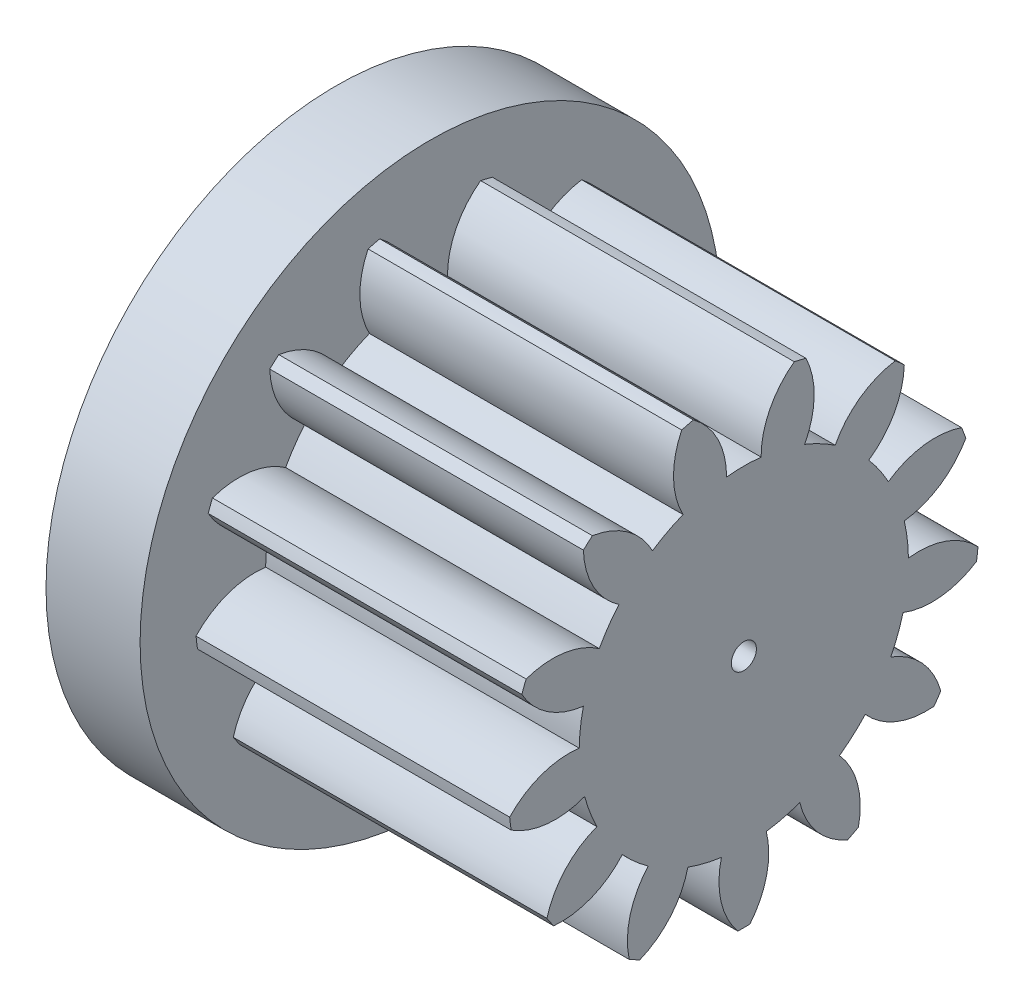
SolidWorks part; units mm, degrees
ref_plane "Plane1" through (0, 0, 0) normal (0, 0, 1) x (1, 0, 0)
ref_plane "Plane2" through (0, 0, 0) normal (0, 1, 0) x (1, 0, 0)
ref_plane "Plane3" through (0, 0, 0) normal (1, 0, 0) x (0, 0, -1)
sketch "HoldingSke" plane through (0, 0, 0) normal (0, 1, 0) x (1, 0, 0)
  line L0 (0, 0) -> (0.9744, -0.225)
  line L1 (-15, 0) -> (100, 0) construction
  line L2 (0, 0) -> (-2.1039, 2.3779)
  line L3 (0, 0) -> (-11.863, 4.5341)
  line L4 (0, 0) -> (8.4147, 1.9427)
  line L5 (0, 0) -> (-46.8476, -17.4728)
  line L6 (0, 0) -> (-8.2896, -5.593)
  line L7 (-2.1039, 2.3779) -> (8.6586, 51.2059)
  line L8 (-76.2, 54.61) -> (-76.1, 54.61)
  line L9 (-71.009, 38.7566) -> (-53.1078, 45.2721)
  line L10 (-76.2, 71.12) -> (104.1128, 71.12)
  line L11 (0, 0) -> (-10, 0)
  line L12 (-76.2, 101.6) -> (-76.162, 101.6)
  line L13 (24.9733, 27.94) -> (52.9518, 28.4284)
  line L14 (24.9733, 27.94) -> (24.9743, 27.94)
  line L15 (24.9733, 27.94) -> (100.4006, 29.5858)
  line L16 (-63.627, -1) -> (-12.827, -1)
  circle A0 centre (0, 0) radius 0.4
  circle A1 centre (0, 0) radius 5.249
  circle A2 centre (0, 0) radius 37.5
  circle A3 centre (0, 0) radius 0.4
  dimension "MHD" = 10.498
  dimension "Hub_dia" = 75
  dimension "Bore" = 0.8
  dimension "MBD" = 0.8
  dimension "Num_teeth" = 13
  dimension "Pitch" = 1
  dimension "Overall_len" = 50
  dimension "Show_teeth" = 13
  dimension "Thickness" = 10
  dimension "OAL" = 50.0001
  dimension "T_dim" = 0.1
  dimension "Ap" = 20
  dimension "H" = 19.05
  dimension "Pitch_radius" = 180.3128
  dimension "Width" = 10
  dimension "Backlash" = 0.038
  dimension "Addendum_fac" = 1
  dimension "Dedendum_fac" = 1.25
  dimension "Clearance_fac" = 0.25
  dimension "Dedendum_add" = 0.001
  dimension "Module" = 1
sketch "BasProSke" plane through (0, 0, 0) normal (0, 1, 0) x (1, 0, 0)
  line L0 (-10, 0) -> (60, 0) construction
  line L1 (0, 0) -> (0, 7.5)
  line L2 (0, 0) -> (10, 0)
  line L3 (10, 0) -> (10, 7.5)
  line L4 (10, 7.5) -> (0, 7.5)
  dimension "Thickness" = 10
  dimension "Diameter" = 15
revolve "Base-Revolve" add sketch "BasProSke" angle 360 about L0
sketch "TooCutSke" plane through (0, 0, 0) normal (1, 0, 0) x (0, 0, -1)
  line L1 (0, 0) -> (0, 107) construction
  line L2 (0, 0) -> (-0.8499, 6.4442) construction
  line L3 (0, 0) -> (-3.0921, 12.5452) construction
  line L4 (-0.8499, 6.4442) -> (-1.5461, 6.2726) construction
  arc A0 (0.5505, 5.2201) -> (-0.5505, 5.2201) centre (0, 0) ccw
  arc A1 (1.6352, 7.3456) -> (-1.6352, 7.3456) centre (0, 0) ccw
  circle A2 centre (0, 0) radius 6.5 construction
  circle A3 centre (0, 0) radius 6.108 construction
  arc A4 (-0.5505, 5.2201) -> (-1.6352, 7.3456) centre (-3.1505, 5.2328) ccw
  arc A5 (1.6352, 7.3456) -> (0.5505, 5.2201) centre (3.1505, 5.2328) ccw
  dimension "Root_dia" = 10.498
  dimension "Overcut_dia" = 15.0508
  dimension "Pitch_dia" = 13
  dimension "Base_dia" = 12.216
  dimension "Flank_rad" = 2.6
  dimension "Half_ang" = 13.846
  dimension "Half_CT" = 0.717
extrude "ToothCut" cut sketch "TooCutSke" along normal through all
fillet "Breaks" [suppressed] radius 0.02
fillet "RootFillets" [suppressed] radius 0.251
pattern_circular "TeethCuts" count 13 every 27.692 about axis through (-10, 0, 0) along (1, 0, 0) of "ToothCut", "RootFillets", "Breaks"
sketch "HubNeaOneSke" plane through (0, 0, 0) normal (-1, 0, 0) x (0, 0, 1)
  circle A0 centre (0, 0) radius 5.249
  dimension "Diameter" = 10.498
extrude "HubNearOne" [suppressed] add sketch "HubNeaOneSke" along normal blind 40.0001
sketch "HubNeaBotSke" plane through (0, 0, 0) normal (-1, 0, 0) x (0, 0, 1)
  circle A0 centre (0, 0) radius 5.249
  dimension "Diameter" = 10.498
extrude "HubNearBoth" [suppressed] add sketch "HubNeaBotSke" along normal blind 20
ref_plane "FarPln" through (10, 0, 0) normal (1, 0, 0) x (0, 0, -1)
sketch "HubFarSke" plane through (10, 0, 0) normal (1, 0, 0) x (0, 0, -1)
  circle A0 centre (0, 0) radius 5.249
  dimension "Diameter" = 10.498
extrude "HubFar" [suppressed] add sketch "HubFarSke" along normal blind 20
sketch "BorSke" plane through (0, 0, 0) normal (1, 0, 0) x (0, 0, -1)
  circle A0 centre (0, 0) radius 0.4
  dimension "Diameter" = 0.8
extrude "Bore" cut sketch "BorSke" along normal mid plane 100.0001
sketch "KeySke" plane through (0, 0, 0) normal (1, 0, 0) x (0, 0, -1)
  line L0 (-0.05, 0) -> (-0.05, 0.5)
  line L1 (-0.05, 0.5) -> (0.05, 0.5)
  line L2 (0.05, 0.5) -> (0.05, 0)
  line L3 (0, 0) -> (0, 34) construction
  line L4 (-0.05, 0) -> (0.05, 0)
  dimension "Offset" = 0.5
  dimension "Width" = 0.1
extrude "Keyway" [suppressed] cut sketch "KeySke" along normal mid plane 100.0001
pattern_circular "Keyway2" [suppressed] count 2 every 90 about axis through (-10, 0, 0) along (1, 0, 0)
sketch "Sketch1" plane through (0, 0, 0) normal (-1, 0, 0) x (0, 0, 1)
  circle A0 centre (0, 0) radius 9.25
  dimension "D1" = 18.5
extrude "Boss-Extrude1" add sketch "Sketch1" along normal blind 3
sketch "Sketch5" plane through (10, 0, 0) normal (1, 0, 0) x (0, 0, -1)
  circle A0 centre (2.286, 4.659) radius 0.0594
  circle A1 centre (0, 0) radius 5.249
sketch "Sketch6" plane through (-3, 0, 0) normal (-1, 0, 0) x (0, 0, 1)
  circle A3 centre (-8.0167, -1.7243) radius 0.5
  circle A4 centre (-8.0167, -1.7243) radius 0.5
  dimension "D2" = 0
extrude "Cut-Extrude1" cut sketch "Sketch6" against normal blind 2
pattern_circular "CirPattern1" count 6 over 360 about axis through (0, 0, 0) along (1, 0, 0) of "Cut-Extrude1"
equation "' \"Module@HoldingSke\" = 6.35"
equation "' \"Num_teeth@HoldingSke\" = 12"
equation "' \"Ap@HoldingSke\" =  20"
equation "' \"Ap@HoldingSke\" = 20"
equation "' \"Width@HoldingSke\" = 0.5 * 25.4"
equation "' \"Hub_dia@HoldingSke\"= 1 * 25.4"
equation "' \"Hub_dia@HoldingSke\" = 1 * 25.4"
equation "' \"Overall_len@HoldingSke\" = 1.0 * 25.4"
equation "' \"Bore@HoldingSke\" = 0.75 * 25.4"
equation "' \"T_dim@HoldingSke\" = 0.1 * 25.4"
equation "' \"Width@KeySke\" = 0.25 * 25.4"
equation "' \"Show_teeth@HoldingSke\" = 13"
equation "' \"Backlash@HoldingSke\" = 0.009 * 25.4"
equation "' \"Addendum_fac@HoldingSke\" = 1.0"
equation "' \"Dedendum_fac@HoldingSke\" = 1.25"
equation "' \"Dedendum_add@HoldingSke\" = 0.00005 * 25.4"
equation "' \"Clearance_fac@HoldingSke\" = 0.25"
equation "\"Pitch@HoldingSke\" = 1 / \"Module@HoldingSke\""
equation "\"Overcut_dia@TooCutSke\" = (\"Num_teeth@HoldingSke\" + 2 * \"Addendum_fac@HoldingSke\") / \"Pitch@HoldingSke\" + 0.002 * 25.4"
equation "\"Pitch_dia@TooCutSke\" = \"Num_teeth@HoldingSke\" / \"Pitch@HoldingSke\""
equation "\"Base_dia@TooCutSke\" = \"Num_teeth@HoldingSke\" / \"Pitch@HoldingSke\" * cos((\"Ap@HoldingSke\"  * 3.14159265 / 180))"
equation "\"Root_dia@TooCutSke\" = (\"Num_teeth@HoldingSke\" + 2) / \"Pitch@HoldingSke\" - 2 * (\"Addendum_fac@HoldingSke\" + \"Dedendum_fac@HoldingSke\") / \"Pitch@HoldingSke\" - \"Dedendum_add@HoldingSke\" * 2"
equation "\"Half_ang@TooCutSke\" = 180 / \"Num_teeth@HoldingSke\""
equation "\"Half_CT@TooCutSke\" = \"Num_teeth@HoldingSke\" / \"Pitch@HoldingSke\" * sin((3.14159265 / 2 / \"Num_teeth@HoldingSke\")) / 2 - 7 * \"Backlash@HoldingSke\" / 4"
equation "\"Flank_rad@TooCutSke\" = \"Num_teeth@HoldingSke\" / \"Pitch@HoldingSke\" / 5"
equation "\"Radius@RootFillets\" = \"Clearance_fac@HoldingSke\" / \"Pitch@HoldingSke\" + \"Dedendum_add@HoldingSke\""
equation "\"Break_rad@Breaks\" = 0.02 / \"Pitch@HoldingSke\""
equation "\"Thickness@HoldingSke\" = \"Width@HoldingSke\""
equation "\"OAL@HoldingSke\" = \"Thickness@HoldingSke\""
equation "\"MHD@HoldingSke\" = (\"Num_teeth@HoldingSke\" + 2) / \"Pitch@HoldingSke\" - 2 * (\"Addendum_fac@HoldingSke\" + \"Dedendum_fac@HoldingSke\")  / \"Pitch@HoldingSke\" - \"Dedendum_add@HoldingSke\" * 2"
equation "\"MBD@HoldingSke\" = (\"Num_teeth@HoldingSke\" + 2) / \"Pitch@HoldingSke\" - 2 * (\"Addendum_fac@HoldingSke\" + \"Dedendum_fac@HoldingSke\")  / \"Pitch@HoldingSke\" - \"Dedendum_add@HoldingSke\" * 2 - 0.002 * 25.4"
equation "\"MHD@HoldingSke\" = ((sgn( \"MHD@HoldingSke\" - \"Hub_dia@HoldingSke\" )-1)*( \"MHD@HoldingSke\" - \"Hub_dia@HoldingSke\" ))/-2+ \"Hub_dia@HoldingSke\""
equation "\"MBD@HoldingSke\" = ((sgn( \"MBD@HoldingSke\" - \"Bore@HoldingSke\" )-1)*( \"MBD@HoldingSke\" - \"Bore@HoldingSke\" ))/-2+ \"Bore@HoldingSke\""
equation "\"OAL@HoldingSke\" = ((sgn( \"OAL@HoldingSke\" - \"Overall_len@HoldingSke\" )+1)*( \"OAL@HoldingSke\" - \"Overall_len@HoldingSke\" ))/2 + \"Overall_len@HoldingSke\" + 0.000002 * 25.4"
equation "\"Num_teeth@TeethCuts\" = int( \"Show_teeth@HoldingSke\" ) + 1"
equation "\"Num_teeth@TeethCuts\" = ((sgn( \"Num_teeth@TeethCuts\" - \"Num_teeth@HoldingSke\" )-1)*( \"Num_teeth@TeethCuts\" - \"Num_teeth@HoldingSke\" ))/-2+ \"Num_teeth@HoldingSke\""
equation "\"Num_teeth@TeethCuts\" = ((sgn( \"Num_teeth@TeethCuts\" - 2.0)+1)*( \"Num_teeth@TeethCuts\" - 2.0))/2 +2.0"
equation "\"Angle@TeethCuts\" = 360.0 / \"Num_teeth@HoldingSke\""
equation "\"Diameter@BasProSke\" = (\"Num_teeth@HoldingSke\" + 2 * \"Addendum_fac@HoldingSke\") / \"Pitch@HoldingSke\""
equation "\"Thickness@BasProSke\"  = \"Thickness@HoldingSke\""
equation "' \"Fillet_rad@BasProSke\" =  \"Thickness@HoldingSke\" * 0.05"
equation "' \"Fillet_rad@BasProSke\" = \"Thickness@HoldingSke\" * 0.05"
equation "\"MHD@HoldingSke\" = ((sgn( \"MHD@HoldingSke\" - \"Root_dia@TooCutSke\" )-1)*( \"MHD@HoldingSke\" - \"Root_dia@TooCutSke\" ))/-2+ \"Root_dia@TooCutSke\""
equation "\"Diameter@HubNeaOneSke\" = \"MHD@HoldingSke\""
equation "\"Length@HubNearOne\" = \"OAL@HoldingSke\" - \"Thickness@BasProSke\""
equation "\"Diameter@HubNeaBotSke\" = \"MHD@HoldingSke\""
equation "\"Length@HubNearBoth\" = ( \"OAL@HoldingSke\" - \"Thickness@BasProSke\" ) / 2.0"
equation "\"Thickness@FarPln\" = \"Thickness@BasProSke\""
equation "\"Diameter@HubFarSke\" = \"MHD@HoldingSke\""
equation "\"Length@HubFar\" = ( \"OAL@HoldingSke\" - \"Thickness@BasProSke\" ) / 2.0"
equation "\"Diameter@BorSke\" = \"MBD@HoldingSke\""
equation "\"D1@Bore\" = \"OAL@HoldingSke\" * 2.0"
equation "\"D1@Keyway\" = \"OAL@HoldingSke\" * 2.0"
equation "\"Offset@KeySke\" = \"T_dim@HoldingSke\" + \"MBD@HoldingSke\" / 2.0"
